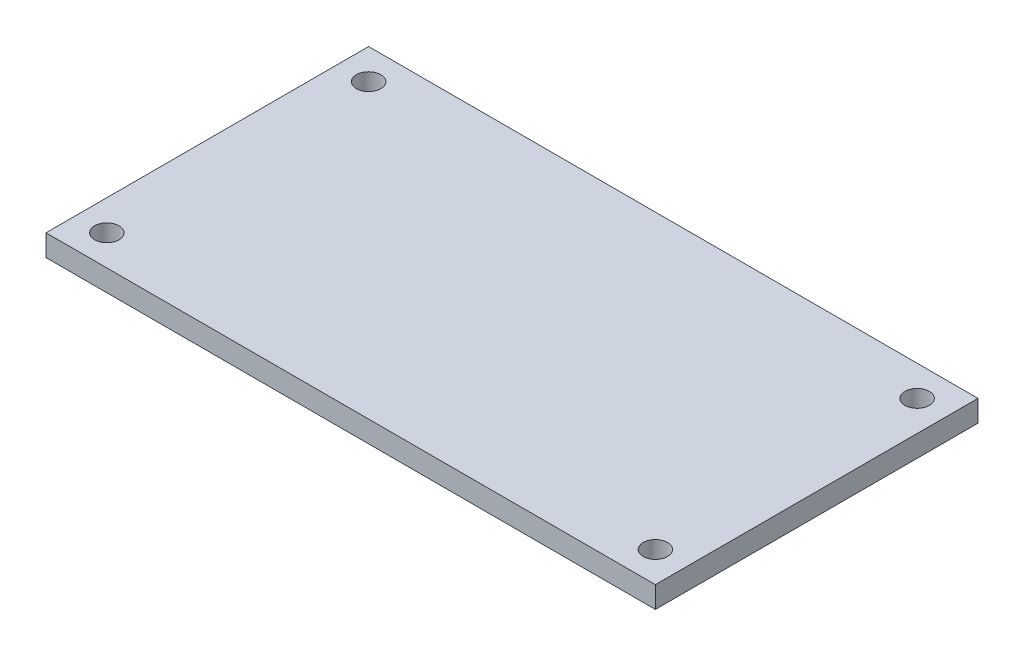
SolidWorks part; units mm, degrees
ref_plane "Front Plane" through (0, 0, 0) normal (0, 0, 1) x (1, 0, 0)
ref_plane "Top Plane" through (0, 0, 0) normal (0, 1, 0) x (1, 0, 0)
ref_plane "Right Plane" through (0, 0, 0) normal (1, 0, 0) x (0, 0, -1)
sketch "Sketch1" plane through (0, 0, 0) normal (0, 1, 0) x (1, 0, 0)
  line L1 (0, 0) -> (85, 0)
  line L2 (0, 0) -> (0, 45)
  line L3 (0, 45) -> (85, 45)
  line L4 (85, 0) -> (85, 45)
  circle A0 centre (4.245, 40.755) radius 1.7
  circle A1 centre (80.755, 40.755) radius 1.7
  circle A2 centre (4.245, 4.245) radius 1.7
  circle A3 centre (80.755, 4.245) radius 1.7
  dimension "D3" = 3.4
  dimension "D4" = 3.4
  dimension "D5" = 76.51
  dimension "D6" = 3.4
  dimension "D7" = 3.4
  dimension "D8" = 36.51
  dimension "D9" = 36.51
  dimension "D10" = 76.51
  dimension "D11" = 4.245
  dimension "D12" = 4.245
  dimension "D13" = 4.245
  dimension "D14" = 4.245
  dimension "D1" = 85
  dimension "D2" = 45
extrude "Boss-Extrude1" add sketch "Sketch1" along normal blind 3
